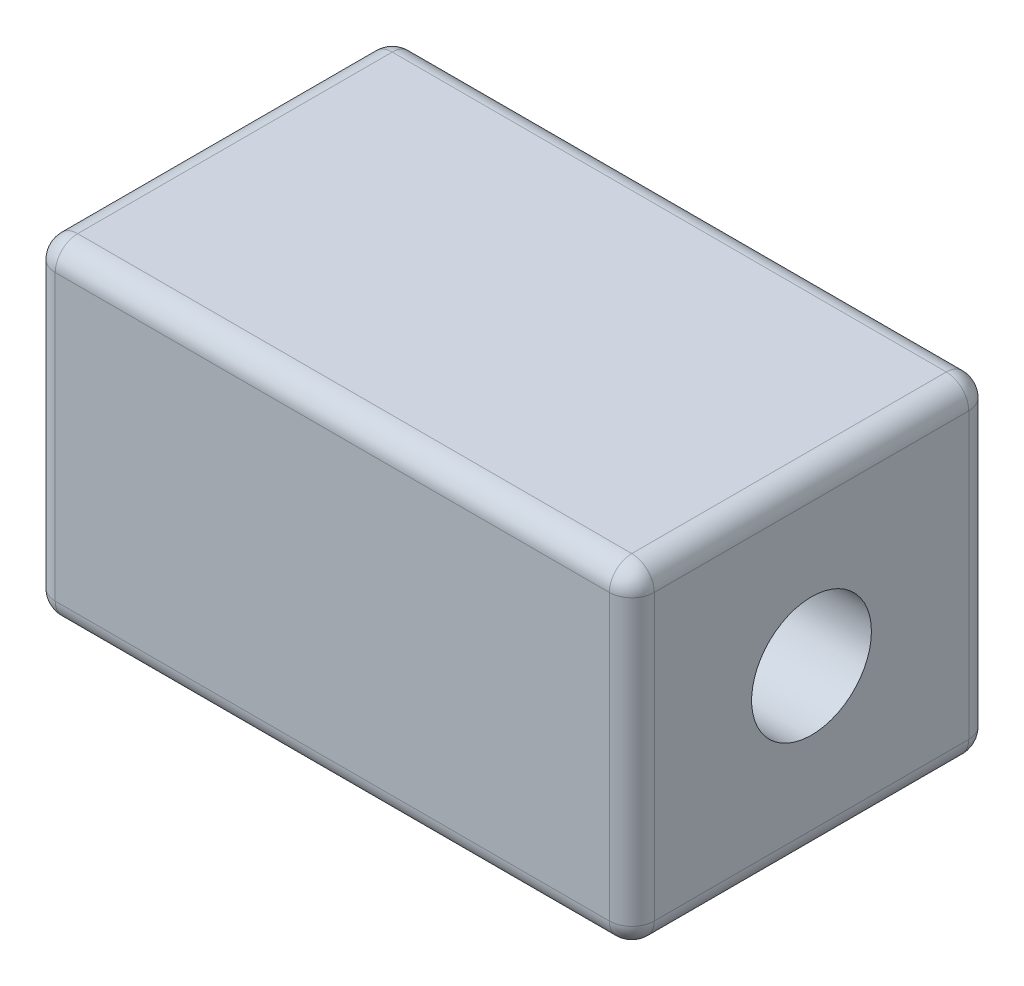
SolidWorks part; units mm, degrees
ref_plane "Front" through (0, 0, 0) normal (0, 0, 1) x (1, 0, 0)
ref_plane "Top" through (0, 0, 0) normal (0, 1, 0) x (1, 0, 0)
ref_plane "Right" through (0, 0, 0) normal (1, 0, 0) x (0, 0, -1)
sketch "Sketch1" plane through (0, 0, 0) normal (0, 1, 0) x (1, 0, 0)
  line L1 (-10, -6) -> (10, -6)
  line L2 (-10, -6) -> (-10, 6)
  line L3 (-10, 6) -> (10, 6)
  line L4 (10, -6) -> (10, 6)
  line L5 (-10, -6) -> (10, 6) construction
  line L6 (-10, 6) -> (10, -6) construction
  point P0 (0, 0)
  dimension "D1" = 12
  dimension "D2" = 20
extrude "Boss-Extrude1" add sketch "Sketch1" along normal blind 11
hole_wizard "Ø1.5 (1.5) Diameter Hole1" positions "Sketch4" profile "Sketch5" hole size "Ø1.5" standard "ANSI Metric"
sketch "Sketch4" plane through (0, 0, 0) normal (0, -1, 0) x (-1, 0, 0)
  line L0 (-10, 0) -> (10, 0) construction
  line L1 (-10, -6) -> (-10, 6) construction
  line L2 (10, 6) -> (10, -6) construction
  point P0 (-5, 3)
  point P2 (5, -3)
  point P17 (5.0502, -4.2292)
  dimension "D1" = 10
  dimension "D2" = 5
  dimension "D3" = 3
  dimension "D4" = 3
sketch "Sketch5" plane through (5, 0, -3) normal (1, 0, 0) x (0, 0, -1)
  line L0 (0, 0) -> (0, 5.8506)
  line L1 (0, 5.8506) -> (0.75, 5.4)
  line L2 (0.75, 5.4) -> (0.75, 0)
  line L5 (0.75, 0) -> (0, 0)
  line L10 (0, 5.8506) -> (-0.75, 5.4) construction
  line L11 (0, -6.35) -> (0, 107.95) construction
  dimension "Hole Dia." = 1.5
  dimension "Hole Depth" = 5.4
  dimension "Drill Angle" = 118
sketch "Sketch6" plane through (10, 0, 0) normal (1, 0, 0) x (0, 0, -1)
  line L0 (0, 11) -> (0, 0) construction
  line L1 (-6, 11) -> (6, 11) construction
  circle A0 centre (0, 5.5) radius 2
  dimension "D1" = 4
extrude "Cut-Extrude1" cut sketch "Sketch6" against normal through all
fillet "Fillet1" radius 0.75 12 edges at (-10, 5.5, 6) (10, 5.5, 6) (0, 0, 6) (0, 11, 6) (-10, 11, 0) (10, 11, 0) (10, 5.5, -6) (0, 11, -6) (-10, 5.5, -6) (0, 0, -6) (10, 0, 0) (-10, 0, 0)
